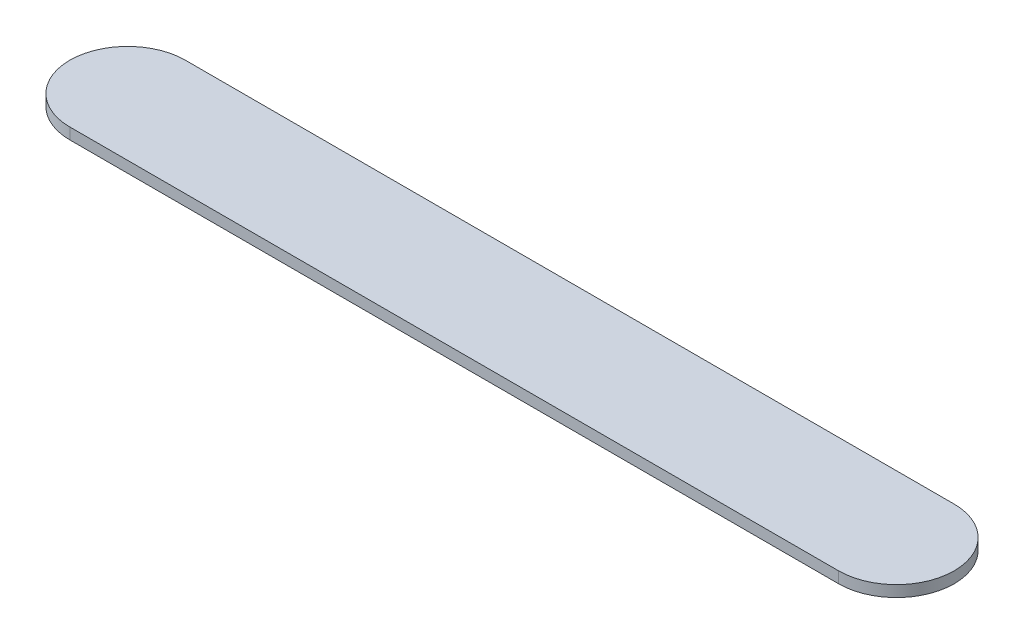
SolidWorks part; units mm, degrees
material "Pine"
ref_plane "Front Plane" through (0, 0, 0) normal (0, 0, 1) x (1, 0, 0)
ref_plane "Top Plane" through (0, 0, 0) normal (0, 1, 0) x (1, 0, 0)
ref_plane "Right Plane" through (0, 0, 0) normal (1, 0, 0) x (0, 0, -1)
sketch "Sketch1" plane through (0, 0, 0) normal (0, 1, 0) x (1, 0, 0)
  line L0 (-68.5046, -7.0738) -> (0, -7.0738)
  line L1 (0, -7.0738) -> (0, 13.5272)
  line L2 (0, 13.5272) -> (-68.5046, 13.5272)
  arc A0 (-68.5046, 13.5272) -> (-68.5046, -7.0738) centre (-68.5046, 3.2267) ccw
extrude "Boss-Extrude1" add sketch "Sketch1" along normal blind 2
mirror "Mirror1" about plane through (0, 2, 7.0738) normal (-1, 0, 0) of bodies 101
